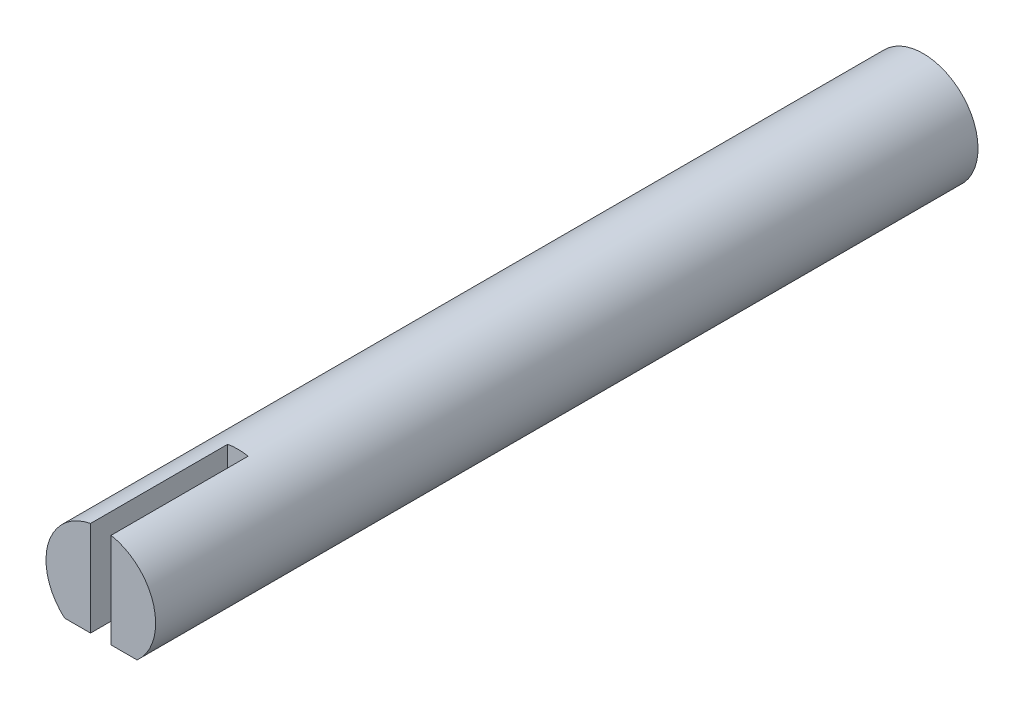
SolidWorks part; units mm, degrees
ref_plane "Front Plane" through (0, 0, 0) normal (0, 0, 1) x (1, 0, 0)
ref_plane "Top Plane" through (0, 0, 0) normal (0, 1, 0) x (1, 0, 0)
ref_plane "Right Plane" through (0, 0, 0) normal (1, 0, 0) x (0, 0, -1)
sketch "Sketch1" plane through (0, 0, 0) normal (0, 0, 1) x (1, 0, 0)
  line L0 (-2.6458, -3) -> (2.6458, -3)
  circle A0 centre (0, 0) radius 4 construction
  arc A1 (2.6458, -3) -> (-2.6458, -3) centre (0, 0) ccw
  dimension "D1" = 8
  dimension "D2" = 3
extrude "Boss-Extrude1" add sketch "Sketch1" along normal blind 60
sketch "Sketch2" plane through (0, 0, 60) normal (0, 0, 1) x (1, 0, 0)
  line L0 (-0.75, -4) -> (-0.75, 4)
  line L1 (-0.75, -4) -> (0.75, -4)
  line L2 (-0.75, 4) -> (0.75, 4)
  line L3 (0.75, -4) -> (0.75, 4)
  line L4 (-0.75, -4) -> (0.75, 4) construction
  line L5 (-0.75, 4) -> (0.75, -4) construction
  point P1 (0, 0)
  dimension "D1" = 1.5
  dimension "D2" = 4
extrude "Cut-Extrude1" cut sketch "Sketch2" against normal blind 10
